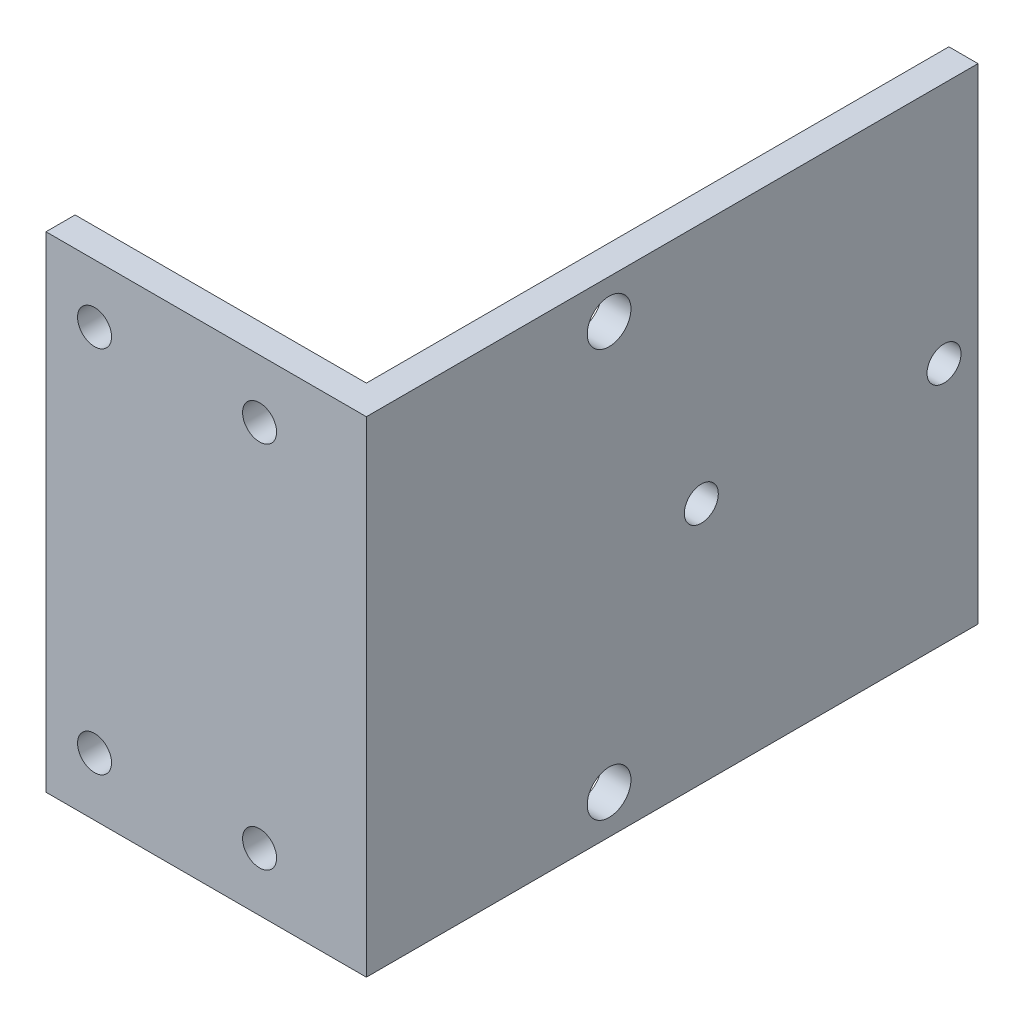
SolidWorks part; units mm, degrees
ref_plane "前视基准面" through (0, 0, 0) normal (0, 0, 1) x (1, 0, 0)
ref_plane "上视基准面" through (0, 0, 0) normal (0, 1, 0) x (1, 0, 0)
ref_plane "右视基准面" through (0, 0, 0) normal (1, 0, 0) x (0, 0, -1)
sketch "草图1" plane through (0, 0, 0) normal (0, 1, 0) x (1, 0, 0)
  line L0 (0, 0) -> (30, 0)
  line L1 (30, 0) -> (30, 60)
  line L2 (0, -3) -> (33, -3)
  line L3 (33, -3) -> (33, 60)
  line L4 (0, -3) -> (0, 0)
  line L5 (30, 60) -> (33, 60)
  dimension "D2" = 30
  dimension "D3" = 60
  dimension "D1" = 3
extrude "凸台-拉伸1" add sketch "草图1" along normal blind 50
sketch "草图2" plane through (0, 0, 0) normal (0, 0, -1) x (-1, 0, 0)
  line L1 (-30, 0) -> (0, 0) construction
  line L2 (-30, 50) -> (-30, 0) construction
  circle A0 centre (-22, 6) radius 1.75
  circle A1 centre (-22, 44) radius 1.75
  circle A2 centre (-5, 44) radius 1.75
  circle A3 centre (-5, 6) radius 1.75
  dimension "D1" = 3.5
  dimension "D2" = 6
  dimension "D3" = 38
  dimension "D4" = 8
  dimension "D5" = 17
  dimension "D6" = 38
extrude "切除-拉伸1" cut sketch "草图2" against normal through all
sketch "草图3" plane through (33, 0, 0) normal (1, 0, 0) x (0, 0, -1)
  line L0 (60, 50) -> (60, 0) construction
  line L1 (-3, 50) -> (60, 50) construction
  circle A0 centre (55, 35) radius 1.75
  circle A1 centre (55, 15) radius 1.75
  circle A2 centre (35, 35) radius 1.75
  circle A3 centre (35, 15) radius 1.75
  dimension "D1" = 3.5
  dimension "D2" = 5
  dimension "D3" = 15
  dimension "D4" = 20
  dimension "D5" = 20
  dimension "D6" = 20
extrude "切除-拉伸2" [suppressed] cut sketch "草图3" against normal up to next
sketch "草图4" plane through (33, 0, 0) normal (1, 0, 0) x (0, 0, -1)
  line L0 (-3, 50) -> (60, 50) construction
  line L1 (60, 50) -> (60, 0) construction
  line L2 (-3, 0) -> (60, 0) construction
  circle A0 centre (56.5, 25) radius 1.75
  circle A1 centre (31.5, 25) radius 1.75
  circle A2 centre (22, 46) radius 2.25
  circle A3 centre (22, 4) radius 2.25
  dimension "D1" = 3.5
  dimension "D2" = 3.5
  dimension "D6" = 4.5
  dimension "D7" = 4.5
  dimension "D3" = 25
  dimension "D4" = 3.5
  dimension "D5" = 25
  dimension "D8" = 42
  dimension "D9" = 4
  dimension "D10" = 38
extrude "切除-拉伸3" cut sketch "草图4" against normal up to next
